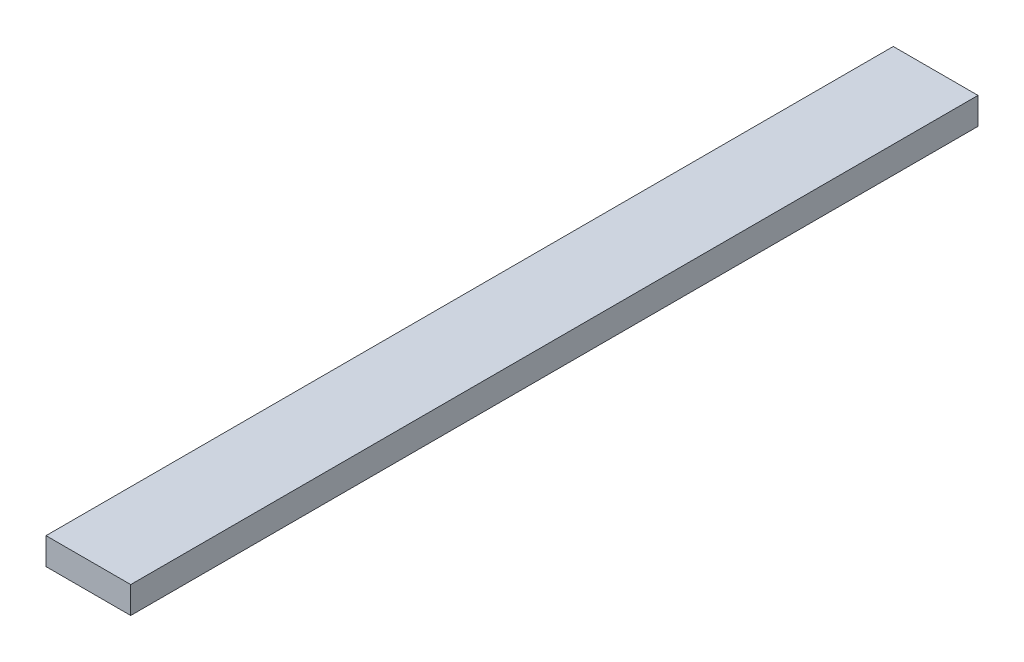
SolidWorks part; units mm, degrees
ref_plane "Płaszczyzna przednia" through (0, 0, 0) normal (0, 0, 1) x (1, 0, 0)
ref_plane "Płaszczyzna górna" through (0, 0, 0) normal (0, 1, 0) x (1, 0, 0)
ref_plane "Płaszczyzna prawa" through (0, 0, 0) normal (1, 0, 0) x (0, 0, -1)
sketch "Sketch1" plane through (0, 0, 0) normal (0, 0, 1) x (1, 0, 0)
  line L1 (0, 0) -> (60, 0)
  line L2 (0, 0) -> (0, 19)
  line L3 (0, 19) -> (60, 19)
  line L4 (60, 0) -> (60, 19)
  line L5 (0, 0) -> (60, 19) construction
  line L6 (0, 19) -> (60, 0) construction
  point P4 (30, 9.5)
  dimension "D1" = 19
  dimension "D2" = 60
extrude "Boss-Extrude1" add sketch "Sketch1" along normal blind 600
sketch "Sketch2" plane through (0, 0, 0) normal (0, -1, 0) x (-1, 0, 0)
  line L0 (0, 0) -> (-60, 0) construction
  line L1 (0, -600) -> (0, 0) construction
  line L2 (0, -600) -> (-60, -600) construction
  circle A0 centre (-38, -8) radius 2.5
  circle A1 centre (-38, -592) radius 2.5
  dimension "D1" = 8
  dimension "D2" = 38
  dimension "D3" = 5
  dimension "D4" = 5
  dimension "D5" = 8
  dimension "D6" = 38
extrude "Cut-Extrude1" cut sketch "Sketch2" against normal blind 10
